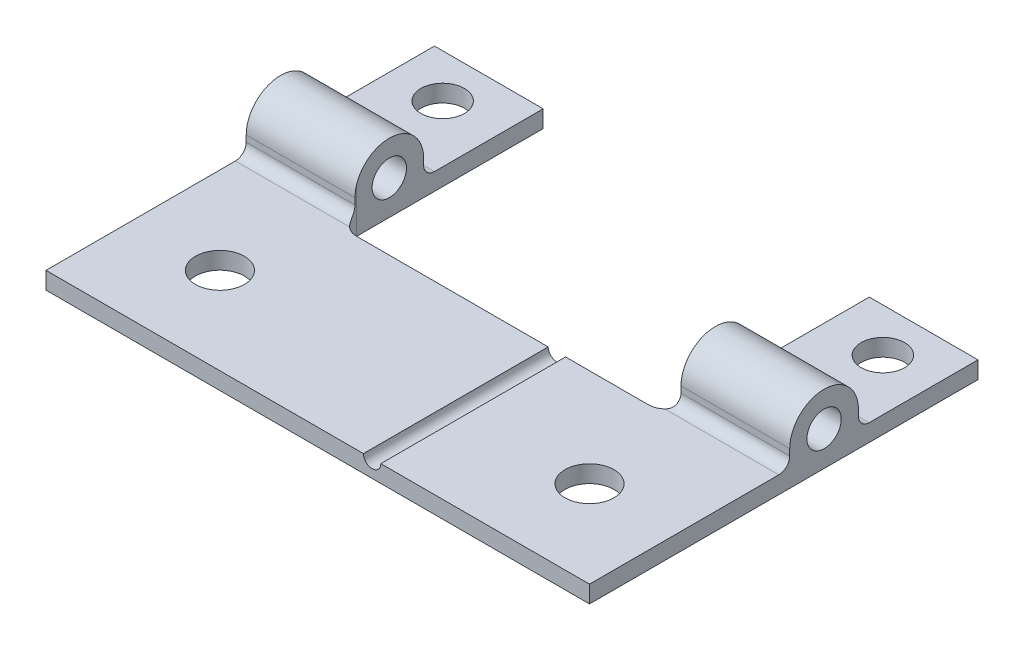
SolidWorks part; units mm, degrees
ref_plane "Front Plane" through (0, 0, 0) normal (0, 0, 1) x (1, 0, 0)
ref_plane "Top Plane" through (0, 0, 0) normal (0, 1, 0) x (1, 0, 0)
ref_plane "Right Plane" through (0, 0, 0) normal (1, 0, 0) x (0, 0, -1)
sketch "Sketch1" plane through (0, 0, 0) normal (0, 1, 0) x (1, 0, 0)
  line L1 (-11.1768, -1.7511) -> (13.8232, -1.7511)
  line L2 (-11.1768, -1.7511) -> (-11.1768, 8.2489)
  line L3 (-11.1768, 8.2489) -> (13.8232, 8.2489)
  line L4 (13.8232, -1.7511) -> (13.8232, 8.2489)
  dimension "D1" = 25
  dimension "D2" = 10
extrude "Base Plate" add sketch "Sketch1" along normal blind 0.79
sketch "Sketch2" plane through (-11.1768, 0, 0) normal (-1, 0, 0) x (0, 0, 1)
  line L0 (-8.2489, 0) -> (-9.0389, 0)
  line L2 (-8.2489, 0.79) -> (-9.0389, 0.79) construction
  line L4 (-8.2489, 0) -> (-8.2489, 0.79)
  line L7 (-7.4589, 0.79) -> (-8.2489, 0.79)
  line L10 (-8.2489, 0.79) -> (-7.4589, 0.79)
  line L12 (-8.2489, 1.58) -> (-8.2489, 0.79) construction
  line L13 (-7.4589, 1.58) -> (-7.4589, 0.79)
  line L14 (-8.2489, 0.79) -> (-7.4589, 0.79)
  line L15 (-10.6189, 1.58) -> (-10.6189, 0) construction
  line L16 (-8.2489, 0) -> (-11.4266, 0)
  line L17 (-8.2489, 0) -> (-8.2489, 0.79)
  line L18 (-8.2489, 0.79) -> (-9.0389, 0.79) construction
  line L20 (-10.6189, 1.58) -> (-10.6189, 1.29)
  line L23 (-11.4266, 0) -> (-16.1189, 0)
  line L24 (-16.1189, 0.79) -> (-16.1189, 0)
  line L25 (-11.1189, 0.79) -> (-16.1189, 0.79)
  arc A4 (-9.0389, 0) -> (-8.2489, 0.79) centre (-9.0389, 0.79) ccw construction
  arc A5 (-8.2489, 1.58) -> (-9.0389, 0.79) centre (-9.0389, 1.58) ccw construction
  arc A6 (-7.4589, 1.58) -> (-10.6189, 1.58) centre (-9.0389, 1.58) ccw
  arc A9 (-11.4089, 0.79) -> (-10.6189, 1.58) centre (-11.4089, 1.58) ccw construction
  arc A10 (-11.1189, 0.79) -> (-10.6189, 1.29) centre (-11.1189, 1.29) ccw
  point P0 (-9.0389, 0)
  point P1 (-8.2489, 0)
  point P6 (-7.4589, 0.79)
  point P9 (-8.2489, 0.79)
  point P10 (-9.0389, 0.79)
  point P12 (-9.0389, 1.58)
  point P16 (-7.4589, 1.58)
  point P18 (-10.4072, 0.79)
  point P19 (-8.2489, 1.58)
  point P21 (-9.0389, 0.79)
  point P22 (-8.2489, 0.79)
  point P23 (-10.6189, 1.58)
  point P26 (-8.2489, 0.79)
  point P31 (-11.4089, 1.58)
  line M20 (1.7511, 0.79) -> (-8.2489, 0.79)
  line M21 (-8.2489, 0.79) -> (-8.2489, 0)
  dimension "D1" = 0.5
  dimension "D2" = 5
extrude "PinHolder" add sketch "Sketch2" against normal blind 5 contours L13 A6 L0 M21 M20
sketch "Sketch4" plane through (-11.1768, 0, 0) normal (-1, 0, 0) x (0, 0, 1)
  line L0 (-9.0389, 0.79) -> (-7.4589, 0.79) construction
  circle A0 centre (-9.0389, 1.58) radius 0.79
  circle A2 centre (-7.4589, 0.79) radius 0.79 construction
  circle A3 centre (-8.2489, 0.79) radius 0.79 construction
  circle A4 centre (-9.0389, 0.79) radius 0.79 construction
  point P1 (-9.0389, 1.58)
  point P6 (-9.0389, 0.79)
  point P7 (-7.4589, 0.79)
  point P8 (-8.2489, 0.79)
  dimension "D1" = 1.58
extrude "Pin Shaft" cut sketch "Sketch4" against normal through all
sketch "Sketch5" plane through (0, 0.79, 0) normal (0, 1, 0) x (1, 0, 0)
  line L0 (-11.1768, 7.4589) -> (-11.1768, -1.7511) construction
  line L1 (-11.1768, -1.7511) -> (13.8232, -1.7511) construction
  line L2 (13.8232, -1.7511) -> (13.8232, 8.2489) construction
  circle A0 centre (-7.1768, 2.2489) radius 1.125
  circle A1 centre (9.8232, 2.2489) radius 1.125
  dimension "D5" = 2.25
  dimension "D6" = 2.25
  dimension "D1" = 4
  dimension "D2" = 4
  dimension "D3" = 4
  dimension "D4" = 4
extrude "Screw Holes" cut sketch "Sketch5" against normal blind 4
sketch "Sketch7" plane through (0, 0, 1.7511) normal (0, 0, 1) x (1, 0, 0)
  line L0 (1.3232, 0) -> (1.3232, 0.79) construction
  line L1 (-11.1768, 0.79) -> (13.8232, 0.79)
  line L2 (-11.1768, 0.79) -> (-11.1768, 0)
  line L3 (-11.1768, 0) -> (13.8232, 0)
  line L4 (13.8232, 0.79) -> (13.8232, 0)
sketch "Sketch11" plane through (0, 0.79, 0) normal (0, 1, 0) x (1, 0, 0)
  line L0 (-6.1768, 11.1189) -> (-6.1768, 16.1189) construction
  line L1 (-11.1768, 16.1189) -> (-6.1768, 16.1189) construction
  line L2 (-11.1768, 16.1189) -> (-11.1768, 12.1189) construction
  line L3 (-11.1768, 12.1189) -> (-6.1768, 12.1189) construction
  line L4 (-6.1768, 16.1189) -> (-6.1768, 12.1189) construction
  circle A0 centre (-8.8018, 14.1189) radius 1
  point P0 (-11.1768, 16.1189)
  point P8 (-8.6768, 16.1189)
  point P9 (-6.1768, 14.1189)
  point P14 (-8.8018, 14.1189)
  dimension "D2" = 2
  dimension "D1" = 4
extrude "Set Screw Hole" cut sketch "Sketch11" against normal blind 1.5 contours A0
ref_plane "Plane1" through (1.3232, 0, 0) normal (1, 0, 0) x (0, 0, -1)
fillet "Mirrored Fillets" radius 0.5 1 edges at (-8.6768, 0.79, -7.4589)
mirror "Mirror1" about plane through (1.3232, 0, 0) normal (1, 0, 0) of "Set Screw Hole", "Pin Shaft", "PinHolder", "Mirrored Fillets"
sketch "Sketch8" plane through (0, 0.79, 0) normal (0, -1, 0) x (1, 0, 0)
  line L0 (8.8232, -8.2489) -> (-6.1768, -8.2489) construction
  line L1 (13.8232, 1.7511) -> (13.8232, -16.1189) construction
  line L2 (3.8232, -8.2489) -> (3.8232, 1.7511)
  line L3 (-11.1768, 1.7511) -> (13.8232, 1.7511) construction
  point P0 (3.8232, -8.2489)
  dimension "D1" = 10
sketch "Sketch9" plane through (0, 0, 1.7511) normal (0, 0, 1) x (1, 0, 0)
  line L0 (13.8232, 0.79) -> (13.8232, 0) construction
  line L3 (-11.1768, 0.79) -> (13.8232, 0.79) construction
  circle A0 centre (3.8232, 0.79) radius 0.4
  point P0 (13.8232, 0)
  point P3 (0, 0)
  point P15 (3.8232, 0.79)
  dimension "D5" = 0.8
  dimension "D1" = 10
sketch "Sketch10" plane through (0, 0, -8.2489) normal (0, 0, -1) x (-1, 0, 0)
  line L0 (11.1768, 0.79) -> (-13.8232, 0.79) construction
  line L1 (-3.8232, 0.79) -> (1.1768, 0.79)
  line L3 (-3.8232, 0) -> (1.1768, 0)
  line L5 (11.1768, 0) -> (-13.8232, 0) construction
  line L7 (-8.8232, 0) -> (6.1768, 0) construction
  line L8 (-3.8232, 0) -> (-8.8232, 0)
  line L10 (-3.8232, 0.79) -> (-8.8232, 0.79)
  line L11 (-8.8232, 0) -> (-8.8232, 0.79)
  line L12 (1.1768, 0.79) -> (6.1768, 0.79)
  line L14 (1.1768, 0) -> (6.1768, 0)
  line L15 (6.1768, 0.79) -> (6.1768, 0)
  dimension "D2" = 5
extrude "Spring Groove" cut sketch "Sketch10" against normal blind 1.5
fillet "Fillet2" radius 0.79 2 edges at (-6.1768, 0.395, -6.7489) (8.8232, 0.395, -6.7489)
sweep "Wire Groove" cut profiles "Sketch9" path "Sketch8"
